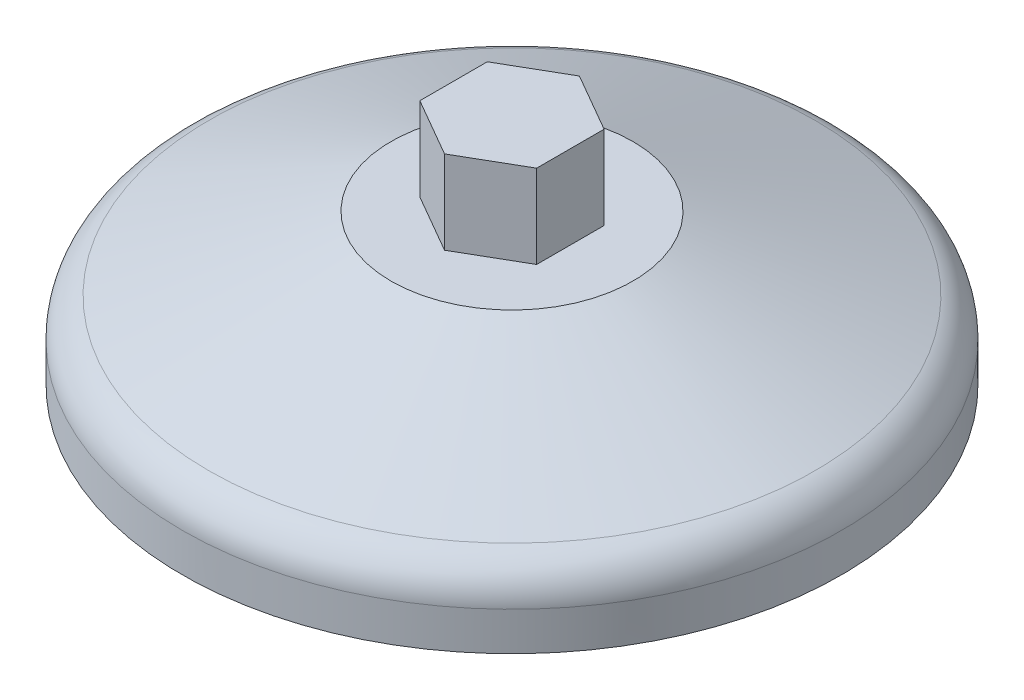
SolidWorks part; units mm, degrees
ref_plane "Front Plane" through (0, 0, 0) normal (0, 0, 1) x (1, 0, 0)
ref_plane "Top Plane" through (0, 0, 0) normal (0, 1, 0) x (1, 0, 0)
ref_plane "Right Plane" through (0, 0, 0) normal (1, 0, 0) x (0, 0, -1)
ref_plane "Plane1" through (0, 0, -4.9601) normal (0, 0, 1) x (1, 0, 0)
sketch "Sketch1" plane through (0, 0, -4.9601) normal (0, 0, 1) x (1, 0, 0)
  line L0 (-40.6775, -48.5554) -> (-55.1775, -48.5554)
  line L1 (-55.1775, -48.5554) -> (-55.1775, -66.5554)
  line L2 (-55.1775, -66.5554) -> (-15.6775, -66.5554)
  line L3 (-15.6775, -66.5554) -> (-15.6775, -58.5554)
  line L4 (-15.6775, -58.5554) -> (-40.6775, -48.5554)
  line L5 (-55.1775, -48.5554) -> (-55.1775, -66.5554) construction
revolve "Revolve1" add sketch "Sketch1" angle 360 about L5
sketch "Sketch2" plane through (0, -48.5554, 0) normal (0, 1, 0) x (-1, 0, 0)
  line L0 (55.1775, 3.1228) -> (62.1775, -0.9187)
  line L1 (62.1775, -0.9187) -> (62.1775, -9.0016)
  line L2 (62.1775, -9.0016) -> (55.1775, -13.043)
  line L3 (55.1775, -13.043) -> (48.1775, -9.0016)
  line L4 (48.1775, -9.0016) -> (48.1775, -0.9187)
  line L5 (48.1775, -0.9187) -> (55.1775, 3.1228)
extrude "Boss-Extrude1" add sketch "Sketch2" along normal blind 10
fillet "Fillet1" radius 5 1 edges at (-55.1775, -58.5554, -44.4601)
